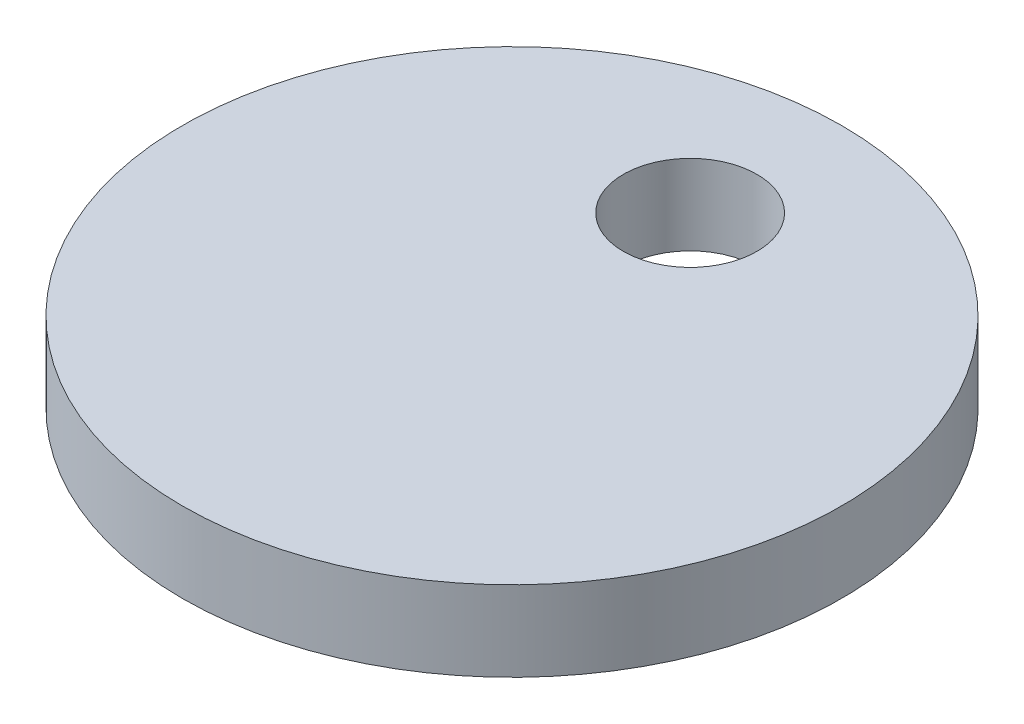
SolidWorks part; units mm, degrees
ref_plane "Front Plane" through (0, 0, 0) normal (0, 0, 1) x (1, 0, 0)
ref_plane "Top Plane" through (0, 0, 0) normal (0, 1, 0) x (1, 0, 0)
ref_plane "Right Plane" through (0, 0, 0) normal (1, 0, 0) x (0, 0, -1)
sketch "Sketch1" plane through (0, 0, 0) normal (0, 1, 0) x (1, 0, 0)
  circle A0 centre (0, 0) radius 7.4
  dimension "D1" = 14.8
extrude "Boss-Extrude1" add sketch "Sketch1" along normal blind 1.8
sketch "Sketch2" plane through (0, 1.8, 0) normal (0, 1, 0) x (1, 0, 0)
  circle A0 centre (0, 4) radius 1.5
  dimension "D1" = 3
  dimension "D2" = 4
extrude "Cut-Extrude1" cut sketch "Sketch2" against normal blind 1.8
